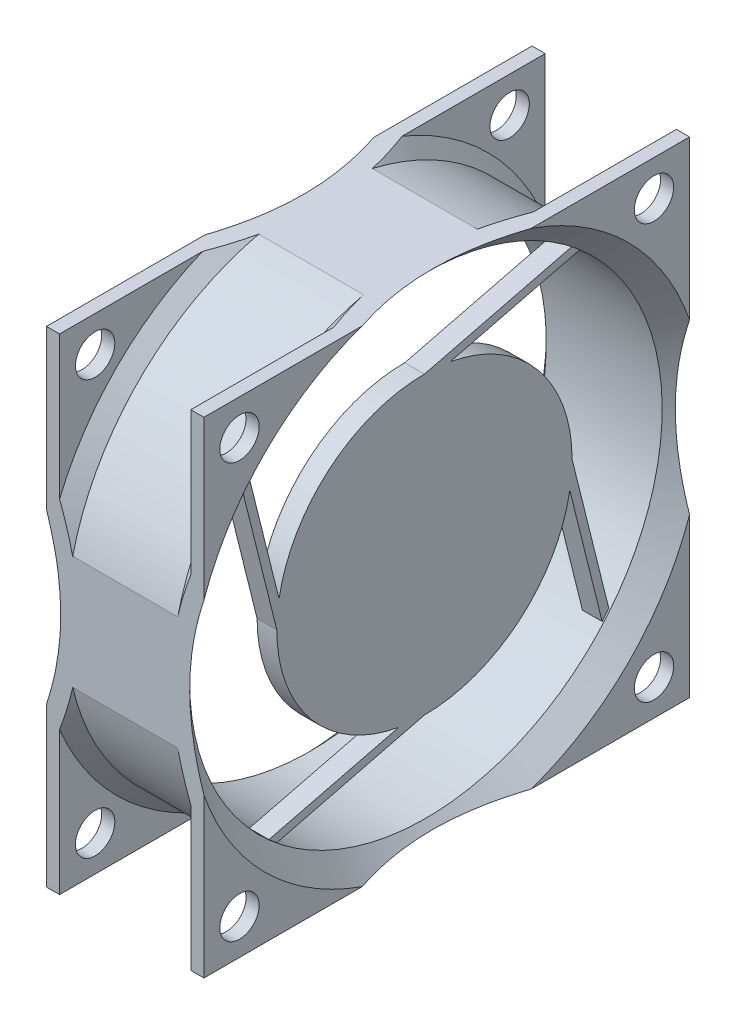
SolidWorks part; units mm, degrees
ref_plane "Front Plane" through (0, 0, 0) normal (0, 0, 1) x (1, 0, 0)
ref_plane "Top Plane" through (0, 0, 0) normal (0, 1, 0) x (1, 0, 0)
ref_plane "Right Plane" through (0, 0, 0) normal (1, 0, 0) x (0, 0, -1)
sketch "Sketch1" plane through (0, 0, 0) normal (0, 0, 1) x (1, 0, 0)
  line L0 (0, 0) -> (37.156, 0) construction
  line L1 (0, 19) -> (4, 19)
  line L2 (4, 19) -> (5, 20)
  line L3 (5, 20) -> (5, 34.9973)
  line L4 (0, 18) -> (4.4142, 18)
  line L5 (4.4142, 18) -> (6, 19.5858)
  line L6 (6, 19.5858) -> (6, 34.9973)
  line L7 (5, 34.9973) -> (6, 34.9973)
  line L8 (0, 0) -> (0, 20.0873) construction
  line L9 (-6, 19.5858) -> (-6, 34.9973)
  line L10 (-4.4142, 18) -> (-6, 19.5858)
  line L11 (-4, 19) -> (-5, 20)
  line L12 (-5, 20) -> (-5, 34.9973)
  line L13 (-6, 34.9973) -> (-5, 34.9973)
  line L14 (-4, 19) -> (0, 19)
  line L15 (-4.4142, 18) -> (0, 18)
  dimension "D1" = 19
  dimension "D2" = 1
  dimension "D3" = 135
  dimension "D5" = 12
  dimension "D4" = 1
revolve "Revolve1" add sketch "Sketch1" angle 360 about L0
sketch "Sketch2" plane through (6, 0, 0) normal (1, 0, 0) x (0, 0, -1)
  line L5 (-71.0416, 64.4374) -> (64.0601, 64.4374)
  line L6 (-71.0416, 64.4374) -> (-71.0416, -60.475)
  line L7 (-71.0416, -60.475) -> (64.0601, -60.475)
  line L8 (64.0601, 64.4374) -> (64.0601, -60.475)
  line L9 (18.5, -18.5) -> (-18.5, -18.5)
  line L10 (18.5, -18.5) -> (18.5, 18.5)
  line L11 (18.5, 18.5) -> (-18.5, 18.5)
  line L12 (-18.5, -18.5) -> (-18.5, 18.5)
  line L13 (18.5, -18.5) -> (-18.5, 18.5) construction
  line L14 (18.5, 18.5) -> (-18.5, -18.5) construction
  point P8 (0, 0)
extrude "Cut-Extrude1" cut sketch "Sketch2" against normal through all
ref_plane "Plane1" through (0, 0, 0) normal (0, -0.7071, 0.7071) x (1, 0, 0)
sketch "Sketch5" plane through (0, 0, 0) normal (0, -0.7071, 0.7071) x (1, 0, 0)
  line L0 (-19.6212, 48.5) -> (20.1845, 48.5) construction
  line L1 (0, 0) -> (37.156, 0) construction
  dimension "D1" = 48.5
ref_plane "Plane2" through (0, 34.2947, 34.2947) normal (0, -0.7071, -0.7071) x (-1, 0, 0)
sketch "Sketch7" plane through (-6, 0, 0) normal (-1, 0, 0) x (0, 0, 1)
  line L0 (0, 0) -> (58.515, 0) construction
  line L2 (0, 0) -> (0, 42.3953) construction
  circle A0 centre (15.7927, 15.7917) radius 1.5
  circle A1 centre (15.7927, -15.7917) radius 1.5
  circle A2 centre (-15.7927, -15.7917) radius 1.5
  circle A3 centre (-15.7927, 15.7917) radius 1.5
  dimension "D1" = 3
extrude "Cut-Extrude2" cut sketch "Sketch7" against normal through all
sketch "Sketch8" plane through (6, 0, 0) normal (1, 0, 0) x (0, 0, -1)
  line L0 (0, 11.25) -> (11.25, 14.0512)
  line L1 (11.25, 14.0512) -> (11.8567, 13.5432)
  line L2 (11.8567, 13.5432) -> (1.9576, 11.0784)
  line L3 (11.25, 0) -> (14.0512, -11.25)
  line L4 (13.5432, -11.8567) -> (11.0784, -1.9576)
  line L5 (14.0512, -11.25) -> (13.5432, -11.8567)
  line L6 (0, -11.25) -> (-11.25, -14.0512)
  line L7 (-11.8567, -13.5432) -> (-1.9576, -11.0784)
  line L8 (-11.25, -14.0512) -> (-11.8567, -13.5432)
  line L9 (-11.25, 0) -> (-14.0512, 11.25)
  line L10 (-13.5432, 11.8567) -> (-11.0784, 1.9576)
  line L11 (-14.0512, 11.25) -> (-13.5432, 11.8567)
  arc A0 (0, 11.25) -> (-11.0784, 1.9576) centre (0, 0) ccw
  circle A1 centre (0, 0) radius 18 construction
  arc A2 (-11.25, 0) -> (-1.9576, -11.0784) centre (0, 0) ccw
  arc A3 (0, -11.25) -> (11.0784, -1.9576) centre (0, 0) ccw
  arc A4 (11.25, 0) -> (1.9576, 11.0784) centre (0, 0) ccw
  point P24 (0, 0)
  dimension "D1" = 4
extrude "Extrude8" add sketch "Sketch8" against normal blind 1.5 from offset 1.7 offset against normal yes
